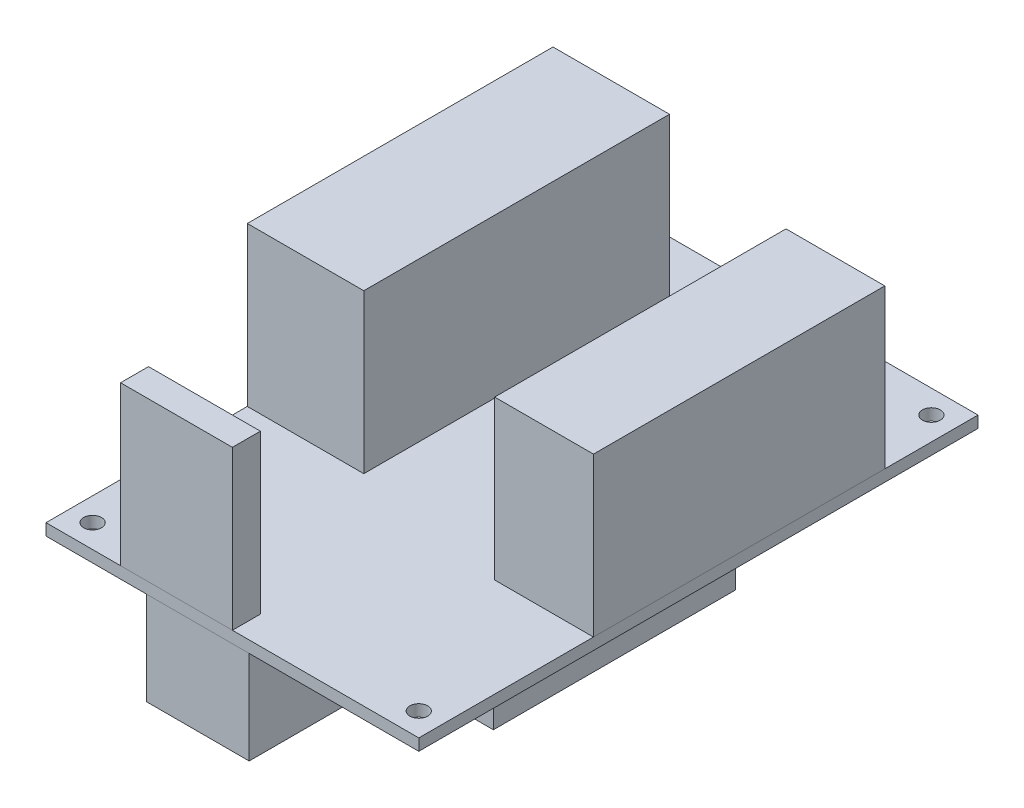
SolidWorks part; units mm, degrees
material "G-10 Garolite"
ref_plane "Front Plane" through (0, 0, 0) normal (0, 0, 1) x (1, 0, 0)
ref_plane "Top Plane" through (0, 0, 0) normal (0, 1, 0) x (1, 0, 0)
ref_plane "Right Plane" through (0, 0, 0) normal (1, 0, 0) x (0, 0, -1)
sketch "Sketch1" plane through (0, 0, 0) normal (0, 1, 0) x (1, 0, 0)
  line L0 (0, 38.1) -> (0, -38.1) construction
  line L1 (-25.4, 38.1) -> (25.4, 38.1)
  line L2 (-25.4, 38.1) -> (-25.4, -38.1)
  line L3 (-25.4, -38.1) -> (25.4, -38.1)
  line L4 (25.4, 38.1) -> (25.4, -38.1)
  line L5 (-22.225, 0) -> (22.225, 0) construction
  line L6 (-22.225, 34.925) -> (22.225, 34.925) construction
  line L7 (-22.225, 34.925) -> (-22.225, -34.925) construction
  line L8 (-22.225, -34.925) -> (22.225, -34.925) construction
  line L9 (22.225, 34.925) -> (22.225, -34.925) construction
  circle A0 centre (-22.225, 34.925) radius 1.2192
  circle A1 centre (22.225, 34.925) radius 1.2192
  circle A2 centre (-22.225, -34.925) radius 1.2192
  circle A3 centre (22.225, -34.925) radius 1.2192
  point P17 (22.225, 36.1442)
  dimension "D3" = 2.4384
  dimension "D1" = 76.2
  dimension "D2" = 50.8
  dimension "D4" = 69.85
  dimension "D5" = 44.45
  dimension "D6" = 1.9558
extrude "Boss-Extrude1" add sketch "Sketch1" along normal blind 1.5875
sketch "Sketch2" plane through (0, 1.5875, 0) normal (0, 1, 0) x (1, 0, 0)
  line L0 (-25.4, 38.1) -> (-25.4, -38.1) construction
  line L1 (-25.4, 30.988) -> (-9.525, 30.988)
  line L2 (-25.4, 30.988) -> (-25.4, -10.668)
  line L3 (-25.4, -10.668) -> (-9.525, -10.668)
  line L4 (-9.525, 30.988) -> (-9.525, -10.668)
  line L5 (11.938, 25.4) -> (25.4, 25.4)
  line L6 (11.938, 25.4) -> (11.938, -14.3002)
  line L7 (11.938, -14.3002) -> (25.4, -14.3002)
  line L8 (25.4, 25.4) -> (25.4, -14.3002)
  line L9 (-15.24, -34.29) -> (0, -34.29)
  line L10 (-15.24, -34.29) -> (-15.24, -38.1)
  line L11 (-15.24, -38.1) -> (0, -38.1)
  line L12 (0, -34.29) -> (0, -38.1)
  line L13 (25.4, -38.1) -> (25.4, 38.1) construction
  line L14 (25.4, 38.1) -> (-25.4, 38.1) construction
  line L15 (-25.4, -38.1) -> (25.4, -38.1) construction
  point P16 (-25.4, 28.9199)
  point P17 (25.4, 27.2161)
  point P20 (-11.9467, -38.1)
  dimension "D1" = 15.875
  dimension "D2" = 13.462
  dimension "D3" = 52.4002
  dimension "D4" = 12.7
  dimension "D5" = 7.112
  dimension "D6" = 48.768
  dimension "D7" = 3.81
  dimension "D8" = 15.24
  dimension "D9" = 10.16
extrude "Boss-Extrude2" add sketch "Sketch2" along normal blind 21.59 separate body
sketch "Sketch3" plane through (0, 0, 0) normal (0, -1, 0) x (1, 0, 0)
  line L0 (-25.4, 38.1) -> (25.4, 38.1) construction
  line L1 (-11.684, 38.1) -> (2.286, 38.1)
  line L2 (-11.684, 38.1) -> (-11.684, -22.098)
  line L3 (-11.684, -22.098) -> (2.286, -22.098)
  line L4 (2.286, 38.1) -> (2.286, -22.098)
  line L5 (2.54, 17.78) -> (15.24, 17.78)
  line L6 (2.54, 17.78) -> (2.54, -15.24)
  line L7 (2.54, -15.24) -> (15.24, -15.24)
  line L8 (15.24, 17.78) -> (15.24, -15.24)
  line L9 (-25.4, -38.1) -> (-25.4, 38.1) construction
  line L10 (25.4, 38.1) -> (25.4, -38.1) construction
  point P10 (-14.3927, 38.1)
  dimension "D1" = 13.97
  dimension "D2" = 60.198
  dimension "D3" = 12.7
  dimension "D4" = 33.02
  dimension "D5" = 20.32
  dimension "D6" = 13.716
  dimension "D7" = 10.16
extrude "Boss-Extrude3" add sketch "Sketch3" along normal blind 12.7 separate body
